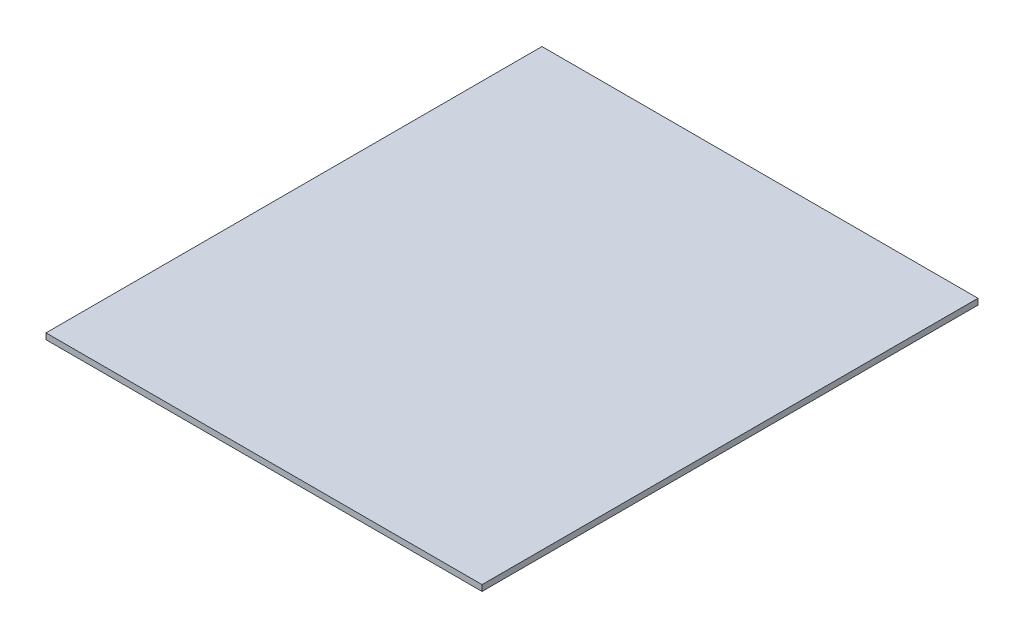
SolidWorks part; units mm, degrees
ref_plane "Front" through (0, 0, 0) normal (0, 0, 1) x (1, 0, 0)
ref_plane "Top" through (0, 0, 0) normal (0, 1, 0) x (1, 0, 0)
ref_plane "Right" through (0, 0, 0) normal (1, 0, 0) x (0, 0, -1)
sketch "Sketch1" plane through (0, 0, 0) normal (0, 1, 0) x (1, 0, 0)
  line L1 (0, 0) -> (219.79, 0)
  line L2 (0, 0) -> (0, 250)
  line L3 (0, 250) -> (219.79, 250)
  line L4 (219.79, 0) -> (219.79, 250)
  dimension "D1" = 219.79
  dimension "D2" = 250
extrude "Boss-Extrude1" add sketch "Sketch1" along normal blind 3
